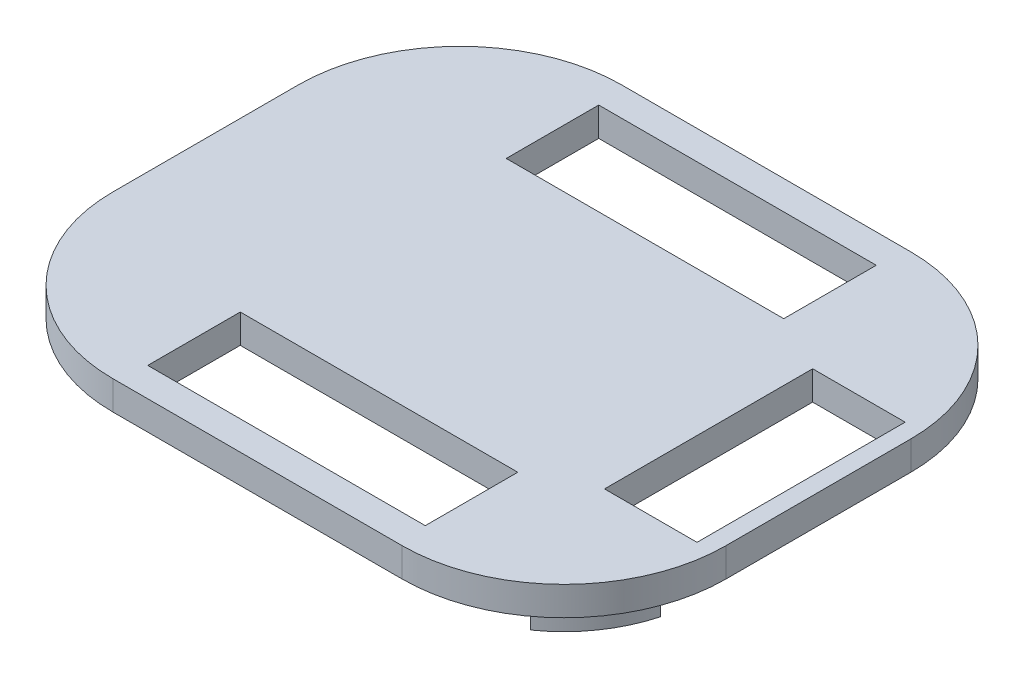
SolidWorks part; units mm, degrees
ref_plane "Front Plane" through (0, 0, 0) normal (0, 0, 1) x (1, 0, 0)
ref_plane "Top Plane" through (0, 0, 0) normal (0, 1, 0) x (1, 0, 0)
ref_plane "Right Plane" through (0, 0, 0) normal (1, 0, 0) x (0, 0, -1)
sketch "Sketch1" plane through (0, 0, 0) normal (0, 1, 0) x (1, 0, 0)
  line L4 (-26.5, 8) -> (-26.5, -8) construction
  line L6 (26.5, -8) -> (26.5, 8) construction
  line L8 (-6.9007, 0) -> (7.9319, 0) construction
  line L9 (0, 7.9961) -> (0, -5.1117) construction
  line L10 (-11.5, -12) -> (11.5, -12) construction
  line L11 (17.5, 8.5) -> (24.5, 8.5) construction
  line L12 (17.5, 8.5) -> (17.5, -8.5) construction
  line L13 (17.5, -8.5) -> (24.5, -8.5) construction
  line L14 (24.5, 8.5) -> (24.5, -8.5) construction
  line L15 (17.5, 8.5) -> (24.5, -8.5) construction
  line L16 (17.5, -8.5) -> (24.5, 8.5) construction
  line L17 (-11.5, 19) -> (11.5, 19) construction
  line L18 (-11.5, 19) -> (-11.5, 12) construction
  line L19 (-11.5, 12) -> (11.5, 12) construction
  line L20 (11.5, 19) -> (11.5, 12) construction
  line L21 (-11.5, 19) -> (11.5, 12) construction
  line L22 (-11.5, 12) -> (11.5, 19) construction
  line L23 (11.5, -19) -> (11.5, -12) construction
  line L24 (-11.5, -19) -> (11.5, -19) construction
  line L25 (-11.5, -19) -> (-11.5, -12) construction
  line L26 (-26.5, 8) -> (-26.5, -8)
  line L27 (-12.5, -22) -> (12.5, -22)
  line L28 (26.5, -8) -> (26.5, 8)
  line L29 (12.5, 22) -> (-12.5, 22)
  line L30 (17, 9) -> (17, -9)
  line L31 (17, -9) -> (25, -9)
  line L32 (25, 9) -> (25, -9)
  line L33 (17, 9) -> (25, 9)
  line L34 (-12, 19.5) -> (-12, 11.5)
  line L35 (-12, 11.5) -> (12, 11.5)
  line L36 (12, 19.5) -> (12, 11.5)
  line L37 (-12, 19.5) -> (12, 19.5)
  line L38 (-12, -11.5) -> (12, -11.5)
  line L39 (12, -19.5) -> (12, -11.5)
  line L40 (-12, -19.5) -> (12, -19.5)
  line L41 (-12, -19.5) -> (-12, -11.5)
  arc A6 (12.5, -22) -> (26.5, -8) centre (12.5, -8) ccw construction
  arc A7 (26.5, 8) -> (12.5, 22) centre (12.5, 8) ccw construction
  arc A8 (-12.5, 22) -> (-26.5, 8) centre (-12.5, 8) ccw
  arc A9 (-26.5, -8) -> (-12.5, -22) centre (-12.5, -8) ccw
  arc A10 (12.5, -22) -> (26.5, -8) centre (12.5, -8) ccw
  arc A11 (26.5, 8) -> (12.5, 22) centre (12.5, 8) ccw
  point P3 (26.5, 0)
  point P29 (21, 0)
  point P34 (0, 15.5)
  dimension "D3" = 16
  dimension "D4" = 14
  dimension "D5" = 0.5
  dimension "D6" = 0.5
  dimension "D2" = 25
  dimension "D7" = 17
  dimension "D8" = 7
  dimension "D9" = 21
  dimension "D10" = 23
  dimension "D11" = 7
  dimension "D12" = 15.5
extrude "Boss-Extrude1" add sketch "Sketch1" along normal blind 2.5
sketch "Sketch2" plane through (0, 0, 0) normal (0, -1, 0) x (1, 0, 0)
  line L8 (0, -19.8) -> (12.5, -19.8) construction
  line L9 (24.3, -8) -> (24.3, 8) construction
  line L10 (12.5, 19.8) -> (0, 19.8) construction
  line L11 (-24.3, 8) -> (-24.3, -8) construction
  line L28 (-12.5, -22) -> (12.5, -22)
  line L29 (26.5, -8) -> (26.5, 8)
  line L30 (12.5, 22) -> (-12.5, 22)
  line L31 (-26.5, 8) -> (-26.5, -8)
  line L32 (0, -22) -> (12.5, -22) construction
  line L33 (26.5, -8) -> (26.5, 8) construction
  line L34 (0, 22) -> (-12.5, 22) construction
  line L35 (-26.5, 8) -> (-26.5, -8) construction
  line L36 (0, -18.05) -> (12.5, -18.05) construction
  line L37 (22.55, -8) -> (22.55, 8) construction
  line L38 (12.5, 18.05) -> (0, 18.05) construction
  line L39 (-22.55, 8) -> (-22.55, -8) construction
  line L40 (0, 27.4773) -> (0, -33.4315) construction
  line L41 (-23.8979, 11.0541) -> (-22.2076, 10.6011)
  line L42 (-18.2644, 16.2325) -> (-19.2682, 17.666)
  line L43 (-23.9681, 16.0301) -> (-12.5, 8) construction
  line L44 (0, 19.8) -> (-12.5, 19.8) construction
  line L45 (12.5, 19.8) -> (-12.5, 19.8) construction
  line L46 (0, 18.05) -> (-12.5, 18.05) construction
  line L47 (12.5, 18.05) -> (-12.5, 18.05) construction
  line L48 (-22.2076, 10.6011) -> (-12.5, 8) construction
  line L49 (-12.5, 8) -> (-18.2644, 16.2325) construction
  line L50 (-12.5, -18.05) -> (0, -18.05) construction
  line L51 (-12.5, -18.05) -> (12.5, -18.05) construction
  line L52 (-12.5, -19.8) -> (0, -19.8) construction
  line L53 (-12.5, -19.8) -> (12.5, -19.8) construction
  line L54 (-12.5, -22) -> (0, -22) construction
  line L55 (-12.5, -22) -> (12.5, -22) construction
  line L56 (12.5, 22) -> (0, 22) construction
  line L57 (12.5, 22) -> (-12.5, 22) construction
  line L58 (23.8979, 11.0541) -> (22.2076, 10.6011)
  line L59 (18.2644, 16.2325) -> (19.2682, 17.666)
  line L60 (-5.3361, 0) -> (5.7904, 0) construction
  line L61 (18.2644, -16.2325) -> (19.2682, -17.666)
  line L62 (23.8979, -11.0541) -> (22.2076, -10.6011)
  line L63 (-23.8979, -11.0541) -> (-22.2076, -10.6011)
  line L64 (-18.2644, -16.2325) -> (-19.2682, -17.666)
  arc A8 (-24.3, -8) -> (-12.5, -19.8) centre (-12.5, -8) ccw construction
  arc A9 (12.5, -19.8) -> (24.3, -8) centre (12.5, -8) ccw construction
  arc A10 (24.3, 8) -> (12.5, 19.8) centre (12.5, 8) ccw construction
  arc A11 (-19.2682, 17.666) -> (-23.8979, 11.0541) centre (-12.5, 8) ccw
  arc A20 (-23.8979, 11.0541) -> (-24.3, 8) centre (-12.5, 8) ccw construction
  arc A21 (-12.5, 19.8) -> (-24.3, 8) centre (-12.5, 8) ccw construction
  arc A22 (-26.5, -8) -> (-12.5, -22) centre (-12.5, -8) ccw
  arc A23 (12.5, -22) -> (26.5, -8) centre (12.5, -8) ccw
  arc A24 (26.5, 8) -> (12.5, 22) centre (12.5, 8) ccw
  arc A25 (-12.5, 22) -> (-26.5, 8) centre (-12.5, 8) ccw
  arc A26 (-26.5, -8) -> (-12.5, -22) centre (-12.5, -8) ccw construction
  arc A27 (12.5, -22) -> (26.5, -8) centre (12.5, -8) ccw construction
  arc A28 (26.5, 8) -> (12.5, 22) centre (12.5, 8) ccw construction
  arc A30 (-22.55, -8) -> (-12.5, -18.05) centre (-12.5, -8) ccw construction
  arc A31 (12.5, -18.05) -> (22.55, -8) centre (12.5, -8) ccw construction
  arc A32 (22.55, 8) -> (12.5, 18.05) centre (12.5, 8) ccw construction
  arc A33 (-18.2644, 16.2325) -> (-22.2076, 10.6011) centre (-12.5, 8) ccw
  arc A34 (-22.2076, 10.6011) -> (-22.55, 8) centre (-12.5, 8) ccw construction
  arc A35 (-12.5, 18.05) -> (-22.55, 8) centre (-12.5, 8) ccw construction
  arc A36 (-12.5, 18.05) -> (-18.2644, 16.2325) centre (-12.5, 8) ccw construction
  arc A37 (-12.5, 19.8) -> (-19.2682, 17.666) centre (-12.5, 8) ccw construction
  arc A38 (-23.9681, 16.0301) -> (-26.5, 8) centre (-12.5, 8) ccw construction
  arc A39 (-12.5, 22) -> (-26.5, 8) centre (-12.5, 8) ccw construction
  arc A40 (18.2644, 16.2325) -> (22.2076, 10.6011) centre (12.5, 8) cw
  arc A41 (19.2682, 17.666) -> (23.8979, 11.0541) centre (12.5, 8) cw
  arc A42 (19.2682, -17.666) -> (23.8979, -11.0541) centre (12.5, -8) ccw
  arc A43 (18.2644, -16.2325) -> (22.2076, -10.6011) centre (12.5, -8) ccw
  arc A44 (-18.2644, -16.2325) -> (-22.2076, -10.6011) centre (-12.5, -8) cw
  arc A45 (-19.2682, -17.666) -> (-23.8979, -11.0541) centre (-12.5, -8) cw
  arc A50 (-12.5, 22) -> (-26.5, 8) centre (-12.5, 8) ccw
  dimension "D3" = 1.75
  dimension "D5" = 35
  dimension "D1" = 0
  dimension "D2" = 2.2
  dimension "D4" = 20
extrude "Boss-Extrude2" add sketch "Sketch2" along normal blind 2.6 contours A43 L61 A42 L62 | A41 L59 A40 L58 | L64 A45 L63 A44 | A33 L41 A11 L42
